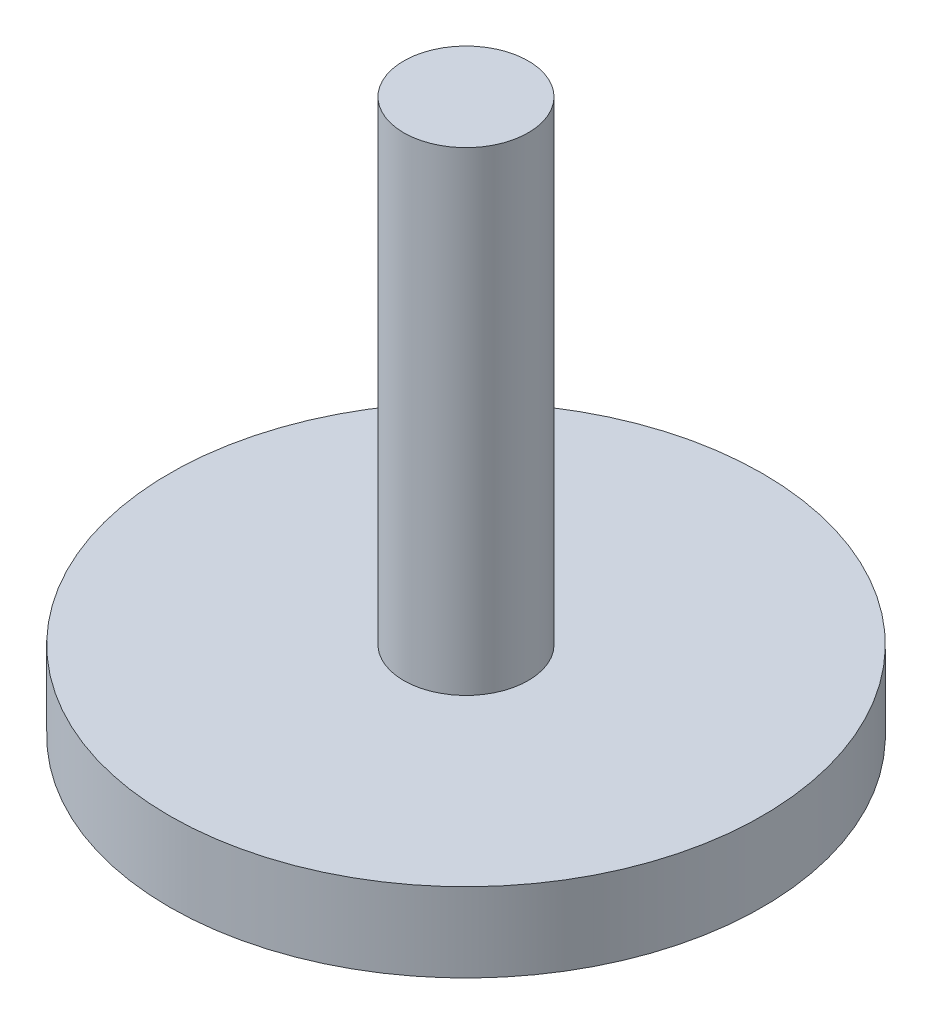
SolidWorks part; units mm, degrees
ref_plane "正面" through (0, 0, 0) normal (0, 0, 1) x (1, 0, 0)
ref_plane "平面" through (0, 0, 0) normal (0, 1, 0) x (1, 0, 0)
ref_plane "右側面" through (0, 0, 0) normal (1, 0, 0) x (0, 0, -1)
sketch "ｽｹｯﾁ1" plane through (0, 0, 0) normal (0, 1, 0) x (1, 0, 0)
  circle A0 centre (0, 0) radius 7.5
  dimension "D1" = 15
extrude "ﾎﾞｽ - 押し出し1" add sketch "ｽｹｯﾁ1" along normal blind 2
sketch "ｽｹｯﾁ2" plane through (0, 2, 0) normal (0, 1, 0) x (1, 0, 0)
  circle A0 centre (0, 0) radius 1.575
  dimension "D1" = 3.15
extrude "ﾎﾞｽ - 押し出し2" add sketch "ｽｹｯﾁ2" along normal blind 12
